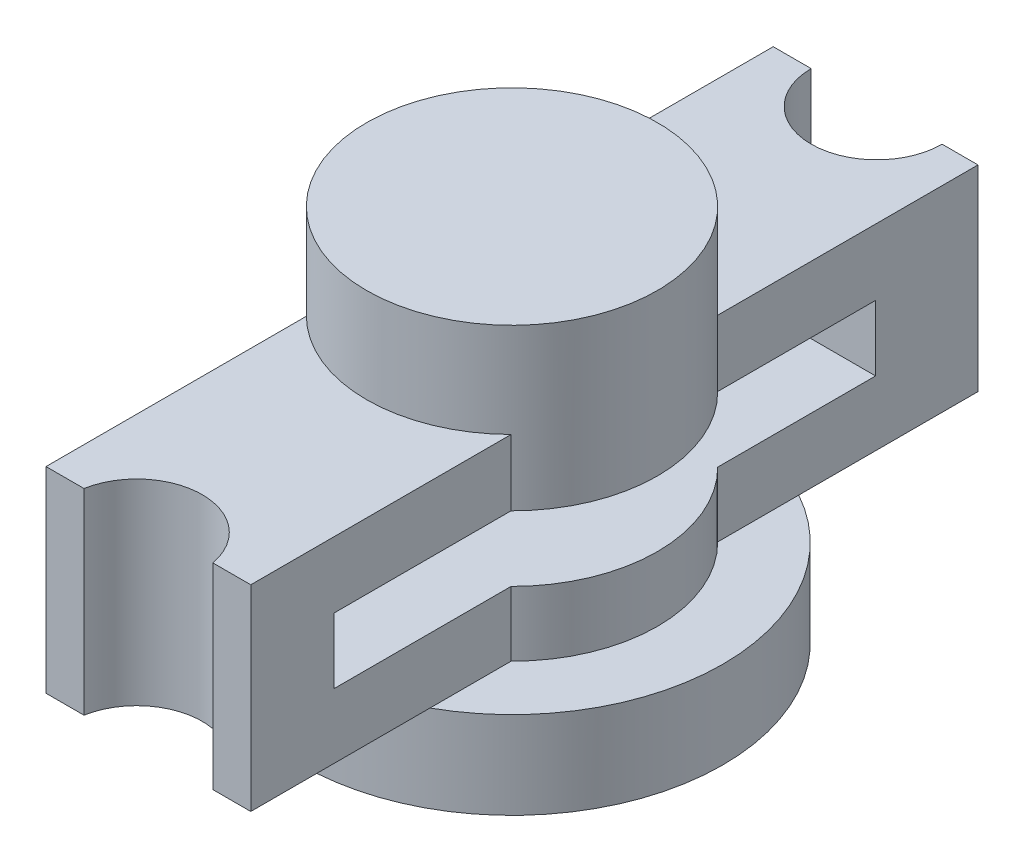
SolidWorks part; units mm, degrees
ref_plane "Front Plane" through (0, 0, 0) normal (0, 0, 1) x (1, 0, 0)
ref_plane "Top Plane" through (0, 0, 0) normal (0, 1, 0) x (1, 0, 0)
ref_plane "Right Plane" through (0, 0, 0) normal (1, 0, 0) x (0, 0, -1)
sketch "Sketch1" plane through (0, 0, 0) normal (0, 1, 0) x (1, 0, 0)
  circle A0 centre (0, 1.0407) radius 20
  dimension "D1" = 40
extrude "Boss-Extrude1" add sketch "Sketch1" against normal blind 52
sketch "Sketch2" plane through (0, -52, 0) normal (0, -1, 0) x (1, 0, 0)
  circle A0 centre (0, -1.0407) radius 29
extrude "Boss-Extrude2" add sketch "Sketch2" along normal blind 12
ref_plane "Plane2" through (0, -52, 0) normal (0, 1, 0) x (1, 0, 0)
sketch "Sketch5" plane through (0, -52, 0) normal (0, 1, 0) x (1, 0, 0)
  line L0 (-14.0783, 15.2464) -> (14.0783, 15.2464)
  line L1 (14.0783, 15.2464) -> (14.0783, 51.0407)
  line L2 (14.0783, 51.0407) -> (-14.0783, 51.0407)
  line L3 (-14.0783, 51.0407) -> (-14.0783, 15.2464)
  line L4 (-14.0783, -13.165) -> (14.0783, -13.165)
  line L5 (14.0783, -13.165) -> (14.0783, -48.9593)
  line L6 (14.0783, -48.9593) -> (-14.0783, -48.9593)
  line L7 (-14.0783, -48.9593) -> (-14.0783, -13.165)
  line L8 (-14.0783, -48.9593) -> (-8.8558, -48.9593)
  line L9 (8.8583, -48.9593) -> (14.0783, -48.9593)
  circle A0 centre (0, 1.0407) radius 20 construction
  circle A1 centre (0, 1.0407) radius 20 construction
  arc A2 (-8.8558, -48.9593) -> (8.8583, -48.9593) centre (0.0012, -50.5571) cw
  arc A3 (9.1442, 51.0407) -> (-8.8558, 51.0407) centre (0.1442, 51.0407) cw
  dimension "D2" = 5.2225
  dimension "D1" = 100
  dimension "D3" = 5.22
extrude "Boss-Extrude3" add sketch "Sketch5" along normal blind 27 contours L6 A2 L5 L4 L7 | L2 A3 L3 L0 L1
sketch "Sketch6" plane through (14.0783, 0, 0) normal (1, 0, 0) x (0, 0, -1)
  line L0 (-13.165, -34.0911) -> (-37.4842, -34.0911)
  line L1 (-13.165, -25) -> (-13.165, -52) construction
  line L2 (-37.4842, -34.0911) -> (-37.4842, -43.0911)
  line L3 (-37.4842, -43.0911) -> (36.9578, -43.0911)
  line L4 (36.9578, -43.0911) -> (36.9578, -34.0911)
  line L5 (36.9578, -34.0911) -> (-13.165, -34.0911)
  line L6 (-37.4842, -38.5911) -> (46.8089, -38.5911) construction
  point P9 (-0.2632, -43.0911)
  dimension "D1" = 4.5
extrude "Cut-Extrude1" cut sketch "Sketch6" against normal through all
sketch "Sketch8" plane through (0, 0, 0) normal (1, 0, 0) x (0, 0, -1)
  line L0 (-13.165, -43.0911) -> (-13.165, -34.0911)
  line L1 (-13.165, -34.0911) -> (15.2464, -34.0911)
  line L2 (15.2464, -34.0911) -> (15.2464, -43.0911)
  line L3 (15.2464, -43.0911) -> (-13.165, -43.0911)
extrude "Cut-Extrude2" cut sketch "Sketch8" against normal mid plane 52 contours L3 L0 L1 L2
sketch "Sketch9" plane through (0, 0, 0) normal (0, 1, 0) x (1, 0, 0)
  circle A0 centre (0, 1.0407) radius 20.0957
extrude "Cut-Extrude3" cut sketch "Sketch9" against normal blind 12
